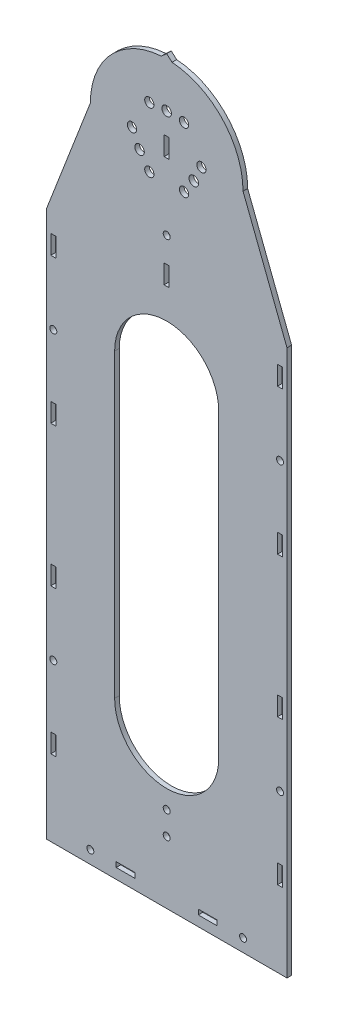
SolidWorks part; units mm, degrees
ref_plane "前视基准面" through (0, 0, 0) normal (0, 0, 1) x (1, 0, 0)
ref_plane "上视基准面" through (0, 0, 0) normal (0, 1, 0) x (1, 0, 0)
ref_plane "右视基准面" through (0, 0, 0) normal (1, 0, 0) x (0, 0, -1)
sketch "草图1" plane through (0, 0, 0) normal (0, 0, 1) x (1, 0, 0)
  line L14 (-51.226, 230.0274) -> (-51.226, 124.4024)
  line L16 (22.524, -1.3476) -> (14.524, 0.6524) construction
  line L18 (19.524, -5.8819) -> (52.774, -5.8819)
  line L19 (0.774, 191.5542) -> (0.774, 61.5542) construction
  line L20 (-33.726, -1.3476) -> (-30.726, 0.6524) construction
  line L21 (0.774, -5.8819) -> (0.774, 9.1181) construction
  line L22 (-20.976, -1.3476) -> (-12.976, 0.6524) construction
  line L24 (53.774, 124.4024) -> (33.4034, 124.4024) construction
  line L35 (-21.076, -1.4476) -> (-12.876, -1.4476)
  line L36 (-12.876, 0.7524) -> (-12.876, -1.4476)
  line L37 (-21.076, 0.7524) -> (-12.876, 0.7524)
  line L38 (-21.076, 0.7524) -> (-21.076, -1.4476)
  line L40 (-51.226, 0.6524) -> (-51.226, -5.8819)
  line L50 (52.774, 0.6524) -> (52.774, 124.4024)
  line L51 (-51.226, 124.4024) -> (-51.226, 0.6524) construction
  line L54 (52.774, 230.0274) -> (52.774, 124.4024)
  line L63 (-54.726, 186.2774) -> (-34.3555, 186.2774) construction
  line L75 (-53.226, 124.4024) -> (-32.8555, 124.4024) construction
  line L81 (0.774, 9.1181) -> (0.774, 19.1181) construction
  line L82 (-51.226, -5.8819) -> (-17.976, -5.8819)
  line L83 (51.774, 62.5274) -> (31.4034, 62.5274) construction
  line L86 (51.774, 124.4024) -> (43.3395, 124.4024) construction
  line L87 (52.774, 124.4024) -> (52.774, 0.6524) construction
  line L89 (35.274, -1.3476) -> (32.274, 0.6524) construction
  line L91 (22.624, 0.7524) -> (22.624, -1.4476)
  line L92 (22.624, 0.7524) -> (14.424, 0.7524)
  line L93 (14.424, 0.7524) -> (14.424, -1.4476)
  line L113 (52.774, 0.6524) -> (52.774, -5.8819)
  line L124 (-17.976, -5.8819) -> (19.524, -5.8819)
  line L125 (-51.226, 124.4024) -> (-51.226, 0.6524)
  line L126 (23.274, 191.5542) -> (23.274, 61.5542)
  line L130 (-21.726, 191.5542) -> (-21.726, 61.5542)
  line L138 (-49.326, 221.8149) -> (-47.126, 221.8149)
  line L139 (-49.326, 221.8149) -> (-49.326, 213.6149)
  line L140 (-49.326, 213.6149) -> (-47.126, 213.6149)
  line L141 (-47.126, 221.8149) -> (-47.126, 213.6149)
  line L142 (-47.126, 150.7399) -> (-47.126, 158.9399)
  line L143 (-49.326, 158.9399) -> (-47.126, 158.9399)
  line L144 (-49.326, 150.7399) -> (-49.326, 158.9399)
  line L145 (-49.326, 150.7399) -> (-47.126, 150.7399)
  line L146 (-49.326, 98.0649) -> (-47.126, 98.0649)
  line L147 (-49.326, 98.0649) -> (-49.326, 89.8649)
  line L148 (-49.326, 89.8649) -> (-47.126, 89.8649)
  line L149 (-47.126, 98.0649) -> (-47.126, 89.8649)
  line L150 (-47.126, 26.9899) -> (-47.126, 35.1899)
  line L151 (-49.326, 35.1899) -> (-47.126, 35.1899)
  line L152 (-49.326, 26.9899) -> (-49.326, 35.1899)
  line L153 (-49.326, 26.9899) -> (-47.126, 26.9899)
  line L161 (22.624, -1.4476) -> (14.424, -1.4476)
  line L162 (0.774, 279.1524) -> (0.774, 314.1524) construction
  line L165 (50.874, 26.9899) -> (48.674, 26.9899)
  line L166 (50.874, 26.9899) -> (50.874, 35.1899)
  line L167 (50.874, 35.1899) -> (48.674, 35.1899)
  line L168 (48.674, 26.9899) -> (48.674, 35.1899)
  line L169 (48.674, 98.0649) -> (48.674, 89.8649)
  line L170 (50.874, 89.8649) -> (48.674, 89.8649)
  line L171 (50.874, 98.0649) -> (50.874, 89.8649)
  line L172 (50.874, 98.0649) -> (48.674, 98.0649)
  line L173 (-49.326, 221.8149) -> (-47.126, 221.8149)
  line L174 (-49.326, 221.8149) -> (-49.326, 213.6149)
  line L175 (-49.326, 213.6149) -> (-47.126, 213.6149)
  line L176 (-47.126, 221.8149) -> (-47.126, 213.6149)
  line L177 (-47.126, 150.7399) -> (-47.126, 158.9399)
  line L178 (-49.326, 158.9399) -> (-47.126, 158.9399)
  line L179 (-49.326, 150.7399) -> (-49.326, 158.9399)
  line L180 (-49.326, 150.7399) -> (-47.126, 150.7399)
  line L181 (53.774, 186.2774) -> (33.4034, 186.2774) construction
  line L182 (50.874, 150.7399) -> (48.674, 150.7399)
  line L183 (50.874, 150.7399) -> (50.874, 158.9399)
  line L184 (50.874, 158.9399) -> (48.674, 158.9399)
  line L185 (48.674, 150.7399) -> (48.674, 158.9399)
  line L186 (48.674, 221.8149) -> (48.674, 213.6149)
  line L187 (50.874, 213.6149) -> (48.674, 213.6149)
  line L188 (50.874, 221.8149) -> (50.874, 213.6149)
  line L189 (50.874, 221.8149) -> (48.674, 221.8149)
  line L190 (50.874, 150.7399) -> (48.674, 150.7399)
  line L191 (50.874, 150.7399) -> (50.874, 158.9399)
  line L192 (50.874, 158.9399) -> (48.674, 158.9399)
  line L193 (48.674, 150.7399) -> (48.674, 158.9399)
  line L194 (48.674, 221.8149) -> (48.674, 213.6149)
  line L195 (50.874, 213.6149) -> (48.674, 213.6149)
  line L196 (50.874, 221.8149) -> (50.874, 213.6149)
  line L197 (50.874, 221.8149) -> (48.674, 221.8149)
  line L200 (33.774, 279.1524) -> (-32.226, 279.1524) construction
  line L202 (33.774, 279.1524) -> (52.774, 230.0274)
  line L205 (-1.528, 312.072) -> (0.774, 314.1524)
  line L206 (0.774, 314.1524) -> (3.0759, 312.072)
  line L207 (0.774, 279.1524) -> (0.774, 246.1524) construction
  line L208 (0.774, 231.1524) -> (0.774, 246.1524) construction
  line L209 (1.874, 227.0524) -> (-0.326, 227.0524)
  line L210 (1.874, 227.0524) -> (1.874, 235.2524)
  line L211 (1.874, 235.2524) -> (-0.326, 235.2524)
  line L212 (-0.326, 227.0524) -> (-0.326, 235.2524)
  line L213 (1.874, 227.0524) -> (-0.326, 235.2524) construction
  line L214 (1.874, 235.2524) -> (-0.326, 227.0524) construction
  line L215 (-0.326, 283.2524) -> (1.874, 283.2524)
  line L216 (-0.326, 283.2524) -> (-0.326, 275.0524)
  line L217 (-0.326, 275.0524) -> (1.874, 275.0524)
  line L218 (1.874, 283.2524) -> (1.874, 275.0524)
  line L219 (-0.326, 283.2524) -> (1.874, 275.0524) construction
  line L220 (-0.326, 275.0524) -> (1.874, 283.2524) construction
  line L221 (-51.226, 230.0274) -> (-32.226, 279.1524)
  circle A2 centre (-32.226, -0.3476) radius 1.5
  circle A23 centre (-48.226, 62.5274) radius 1.5
  circle A26 centre (-48.226, 186.2774) radius 1.5
  circle A47 centre (33.774, -0.3476) radius 1.5
  circle A48 centre (0.774, 279.1524) radius 15 construction
  circle A55 centre (0.774, 279.1524) radius 13.53 construction
  arc A60 (23.274, 191.5542) -> (-21.726, 191.5542) centre (0.774, 191.5542) ccw
  arc A61 (-21.726, 61.5542) -> (23.274, 61.5542) centre (0.774, 61.5542) ccw
  circle A64 centre (49.774, 62.5274) radius 1.5
  circle A65 centre (49.774, 186.2774) radius 1.5
  circle A66 centre (0.774, 21.1181) radius 1.5
  circle A67 centre (0.774, 31.1181) radius 1.5
  circle A68 centre (0.774, 279.1524) radius 33 construction
  arc A69 (33.774, 279.1524) -> (3.0759, 312.072) centre (0.774, 279.1524) ccw
  arc A70 (-32.226, 279.1524) -> (-1.528, 312.072) centre (0.774, 279.1524) cw
  circle A71 centre (-14.226, 279.1524) radius 2
  circle A72 centre (-6.726, 292.1428) radius 2
  circle A73 centre (8.274, 292.1428) radius 2
  circle A74 centre (15.774, 279.1524) radius 2
  circle A75 centre (8.274, 266.162) radius 2
  circle A76 centre (-6.726, 266.162) radius 2
  circle A77 centre (0.774, 292.6824) radius 2.05
  circle A78 centre (12.4913, 272.3874) radius 2.05
  circle A79 centre (-10.9434, 272.3874) radius 2.05
  circle A80 centre (0.774, 246.1524) radius 1.5
  point P64 (0.774, 231.1524)
  point P87 (-51.226, 248.1524)
  point P111 (0.774, 126.5542)
  dimension "D1" = 6
  dimension "D2" = 3
extrude "凸台-拉伸1" add sketch "草图1" along normal blind 2
